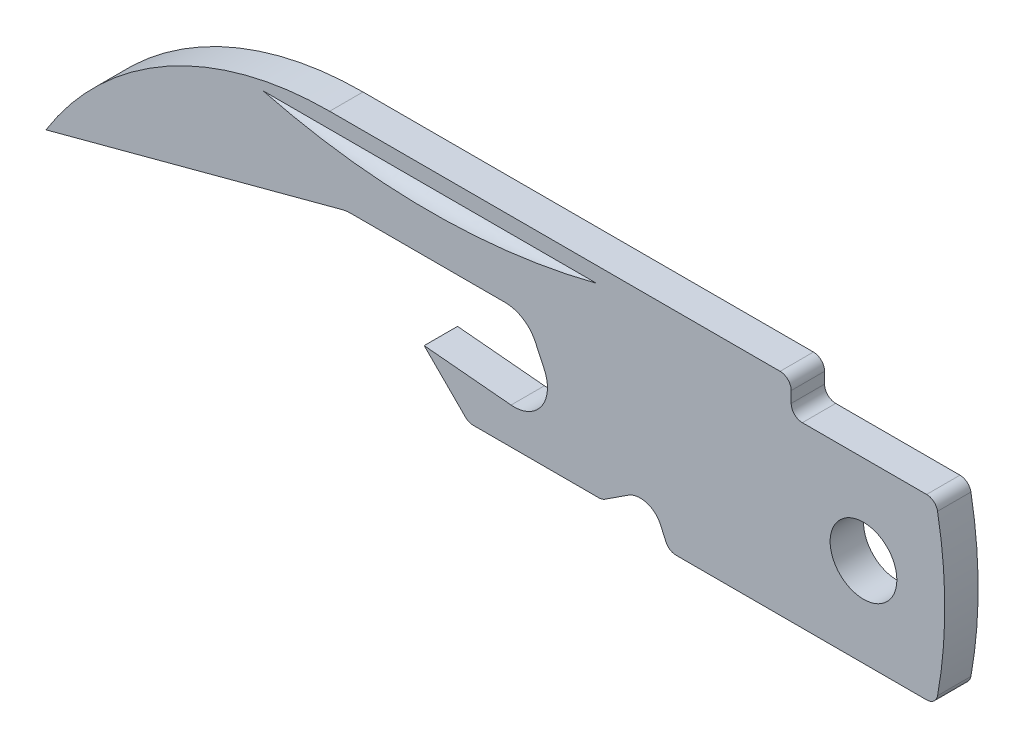
SolidWorks part; units mm, degrees
ref_plane "Front Plane" through (0, 0, 0) normal (0, 0, 1) x (1, 0, 0)
ref_plane "Top Plane" through (0, 0, 0) normal (0, 1, 0) x (1, 0, 0)
ref_plane "Right Plane" through (0, 0, 0) normal (1, 0, 0) x (0, 0, -1)
sketch "Sketch1" plane through (0, 0, 0) normal (0, 0, 1) x (1, 0, 0)
  line L0 (-13, 5.5) -> (-3.25, 5.5)
  line L1 (-3.25, 5.5) -> (-3.25, 4)
  line L2 (-3.25, 4) -> (3.25, 4)
  line L3 (3.25, 4) -> (3.25, -4) construction
  line L4 (3.25, -4) -> (-8.75, -4)
  line L5 (-8.75, -4) -> (-13, 5.5)
  circle A0 centre (0, 0) radius 1.5
  arc A1 (3.25, 4) -> (3.25, -4) centre (-16.3459, 0) cw
  point P8 (3.25, 0)
  point P11 (0, 4)
  dimension "D2" = 3
  dimension "D7" = 20
  dimension "D1" = 1.5
  dimension "D3" = 8
  dimension "D4" = 6.5
  dimension "D5" = 12
  dimension "D6" = 13
extrude "Boss-Extrude1" add sketch "Sketch1" along normal mid plane 1.5
sketch "Sketch7" plane through (0, 0, 0) normal (0, 0, 1) x (1, 0, 0)
  line L0 (-13, 5.5) -> (-24, 5.5)
  line L1 (-36.7511, -1.6) -> (-23.25, 2)
  line L2 (-23.25, 2) -> (-15.15, 2)
  line L3 (-15.15, 2) -> (-13.25, -2.1)
  line L4 (-13.25, -2.1) -> (-19.75, -1.5)
  line L5 (-19.75, -1.5) -> (-17.75, -3.5)
  line L6 (-17.75, -3.5) -> (-11.75, -3.5)
  line L7 (-11.75, -3.5) -> (-9.6, -2.1)
  line L8 (-13, 5.5) -> (-8.75, -4) construction
  line L9 (-9.6, -2.1) -> (-13, 5.5)
  line L10 (-8.75, -4) -> (3.25, -4) construction
  line L11 (-3.25, 4) -> (-3.25, 5.5) construction
  arc A0 (-24, 5.5) -> (-36.7511, -1.6) centre (-24, -9.5) ccw
  dimension "D10" = 15
  dimension "D1" = 0.5
  dimension "D2" = 9
  dimension "D3" = 11
  dimension "D4" = 2
  dimension "D5" = 3
  dimension "D6" = 10
  dimension "D7" = 0.6
  dimension "D8" = 3.4
  dimension "D9" = 3.5
  dimension "D11" = 3.6
  dimension "D12" = 11
  dimension "D13" = 11.5
extrude "Boss-Extrude2" add sketch "Sketch7" along normal mid plane 1.5
fillet "Fillet1" radius 1 1 edges at (-9.6, -2.1, 0)
fillet "Fillet2" radius 0.5 7 edges at (-17.75, -3.5, 0) (-3.25, 5.5, 0) (-3.25, 4, 0) (3.25, 4, 0) (3.25, -4, 0) (-8.75, -4, 0) (-11.75, -3.5, 0)
fillet "Fillet3" radius 1.5 3 edges at (-13.25, -2.1, 0) (-23.25, 2, 0) (-15.15, 2, 0)
sketch "Sketch6" plane through (0, 0, 0.75) normal (0, 0, 1) x (1, 0, 0)
  line L0 (-27, 4.8) -> (-12, 4.8)
  line L1 (-3.75, 5.5) -> (-24, 5.5) construction
  arc A0 (-12, 4.8) -> (-27, 4.8) centre (-19.5, 33.8474) cw
  dimension "D3" = 30
  dimension "D1" = 0.7
  dimension "D2" = 15
  dimension "D4" = 12
revolve "Cut-Revolve1" cut sketch "Sketch6" angle 90 about L0
